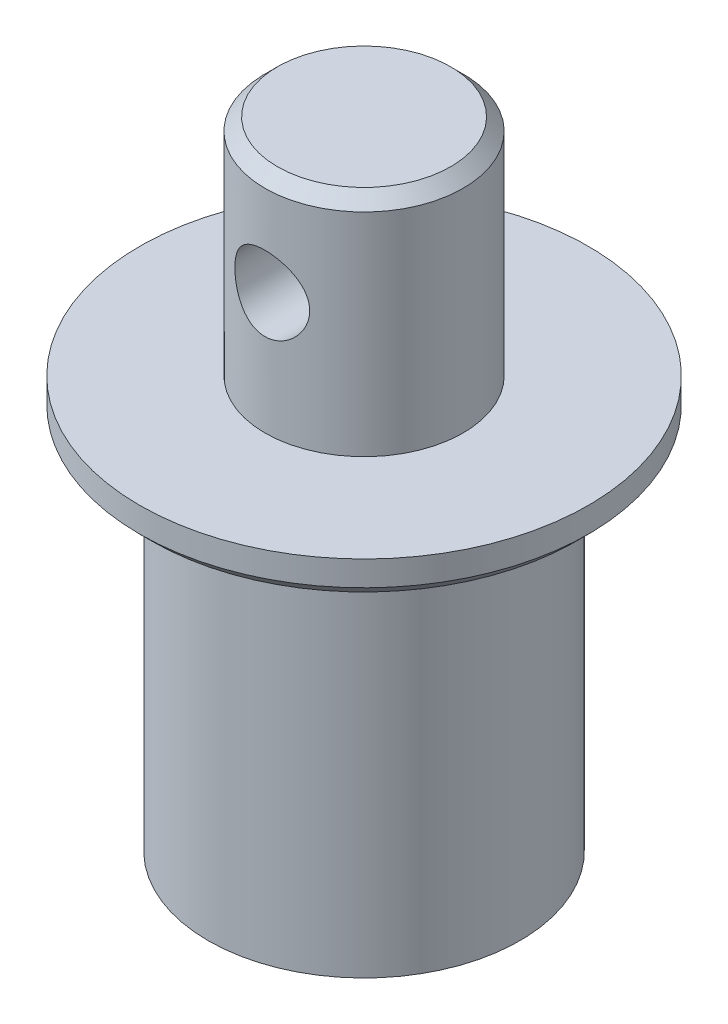
SolidWorks part; units mm, degrees
material "普通碳钢"
ref_plane "前视基准面" through (0, 0, 0) normal (0, 0, 1) x (1, 0, 0)
ref_plane "上视基准面" through (0, 0, 0) normal (0, 1, 0) x (1, 0, 0)
ref_plane "右视基准面" through (0, 0, 0) normal (1, 0, 0) x (0, 0, -1)
sketch "草图1" plane through (0, 0, 0) normal (0, 1, 0) x (1, 0, 0)
  circle A0 centre (0, 0) radius 7.95
  dimension "D1" = 15.9
extrude "凸台-拉伸1" add sketch "草图1" along normal blind 18 contours A0
chamfer "倒角2" distance 1 angle 45 1 edges at (0, 18, 7.95)
sketch "草图4" plane through (0, 0, 0) normal (0, 1, 0) x (1, 0, 0)
  circle A0 centre (0, 0) radius 18
extrude "凸台-拉伸2" add sketch "草图4" against normal blind 3
chamfer "倒角1" distance 1 angle 45 1 edges at (0, -3, 18)
ref_plane "基准面4" through (0, -3, 0) normal (0, -1, 0) x (-1, 0, 0)
sketch "草图5" plane through (0, -3, 0) normal (0, -1, 0) x (-1, 0, 0)
  circle A0 centre (0, 0) radius 12.5
extrude "凸台-拉伸3" add sketch "草图5" along normal blind 30
ref_plane "基准面5" through (0, -33, 0) normal (0, -1, 0) x (-1, 0, 0)
sketch "草图9" plane through (0, 0, 0) normal (0, 0, 1) x (1, 0, 0)
  line L0 (0, -19.8) -> (0, 19.8) construction
  line L1 (19.8, 0) -> (-19.8, 0) construction
  circle A0 centre (0, 9.7) radius 3
  dimension "D1" = 9.7
  dimension "D2" = 6
extrude "切除-拉伸2" cut sketch "草图9" against normal through all both and the other way through all
sketch "草图10" plane through (0, -3, 0) normal (0, -1, 0) x (-1, 0, 0)
  circle A0 centre (0, 0) radius 7.95
extrude "切除-拉伸3" cut sketch "草图10" along normal up to surface (20 mm away) from offset 10 up to face at (0, -33, -12.5)
